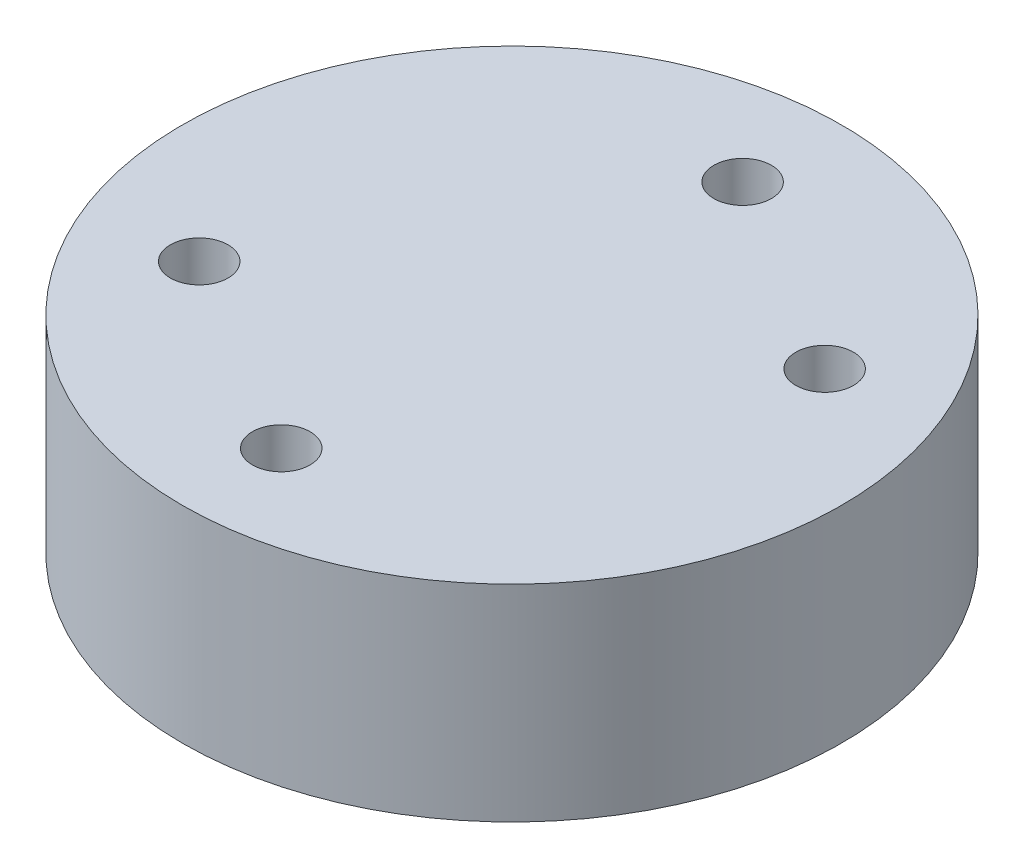
SolidWorks part; units mm, degrees
ref_plane "Front Plane" through (0, 0, 0) normal (0, 0, 1) x (1, 0, 0)
ref_plane "Top Plane" through (0, 0, 0) normal (0, 1, 0) x (1, 0, 0)
ref_plane "Right Plane" through (0, 0, 0) normal (1, 0, 0) x (0, 0, -1)
sketch "Sketch1" plane through (0, 0, 0) normal (0, 1, 0) x (1, 0, 0)
  circle A0 centre (0, 0) radius 10.16
extrude "Boss-Extrude1" add sketch "Sketch1" along normal blind 6.35
sketch "Sketch2" plane through (0, 6.35, 0) normal (0, 1, 0) x (1, 0, 0)
  circle A0 centre (0, 0) radius 7.112
  circle A1 centre (0, -7.112) radius 0.889
  circle A2 centre (0, 7.112) radius 0.889
  circle A7 centre (-6.2539, -3.3867) radius 0.889
  circle A8 centre (6.2539, 3.3867) radius 0.889
sketch "Sketch3" plane through (0, 6.35, 0) normal (0, 1, 0) x (1, 0, 0)
  line L1 (-5.08, 8.7988) -> (-5.08, -8.7988)
  line L2 (-5.08, -8.7988) -> (10.16, 0)
  line L3 (10.16, 0) -> (-5.08, 8.7988)
  circle A0 centre (0, 0) radius 10.16
  circle A1 centre (0, 0) radius 5.08 construction
extrude "Cut-Extrude3" cut sketch "Sketch2" against normal blind 7.62 contours A2 | A8 | A1 | A7
